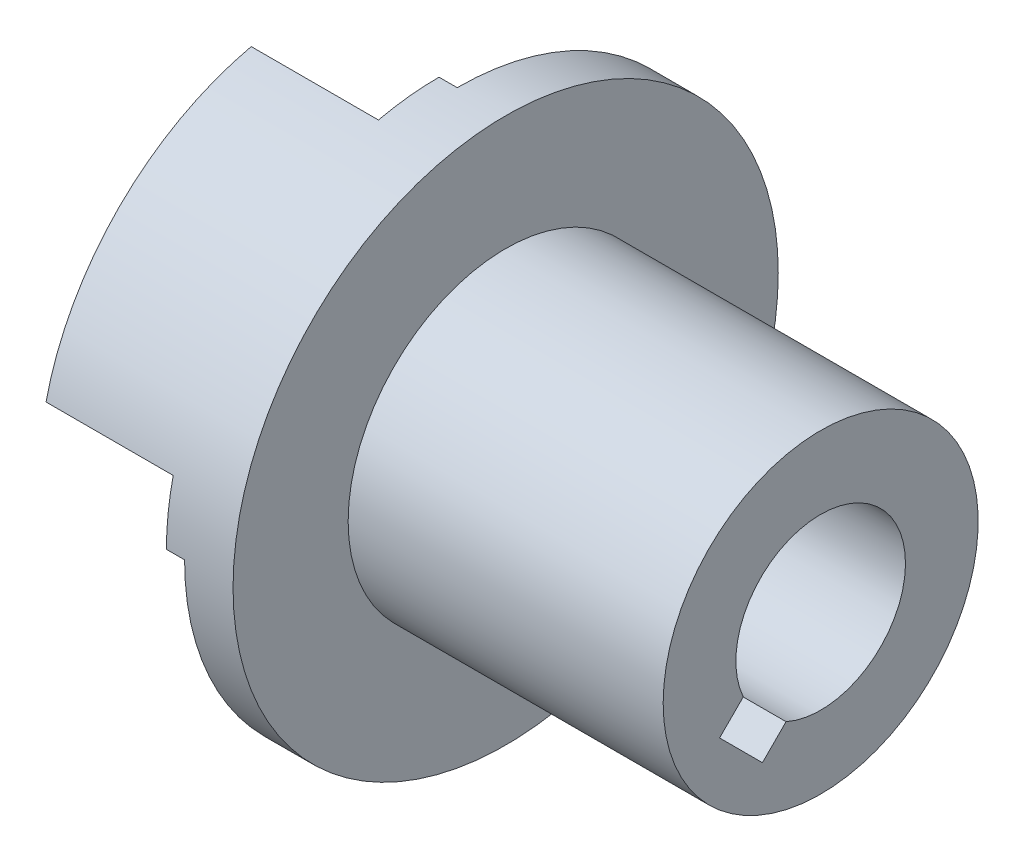
SolidWorks part; units mm, degrees
ref_plane "Спереди" through (0, 0, 0) normal (0, 0, 1) x (1, 0, 0)
ref_plane "Сверху" through (0, 0, 0) normal (0, 1, 0) x (1, 0, 0)
ref_plane "Справа" through (0, 0, 0) normal (1, 0, 0) x (0, 0, -1)
sketch "Эскиз1" plane through (0, 0, 0) normal (0, 0, 1) x (1, 0, 0)
  line L0 (0, 0) -> (112.9286, 0) construction
  line L1 (0, 22.5) -> (0, 7)
  line L2 (0, 7) -> (30, 7)
  line L3 (30, 7) -> (30, 13)
  line L4 (30, 13) -> (4, 13)
  line L5 (4, 13) -> (4, 22.5)
  line L6 (4, 22.5) -> (0, 22.5)
  dimension "l" = 30
  dimension "d1" = 26
  dimension "DD" = 45
  dimension "d" = 14
  dimension "l3" = 4
revolve "Повернуть1" add sketch "Эскиз1" angle 360 about L0
sketch "Эскиз7" plane through (0, 0, 0) normal (-1, 0, 0) x (0, 0, 1)
  line L0 (0, 22.5) -> (0, 14.1421)
  line L1 (22.5, 0) -> (14.1421, 0)
  line L4 (0, 14.1421) -> (14.1421, 0)
  circle A0 centre (0, 0) radius 22.5 construction
  arc A7 (22.5, 0) -> (0, 22.5) centre (0, 0) ccw
  dimension "D1" = 135
  dimension "B1/2" = 10
extrude "Бобышка-Вытянуть4" add sketch "Эскиз7" along normal blind 1.5
sketch "Эскиз9" plane through (-1.5, 0, 0) normal (-1, 0, 0) x (0, 0, 1)
  line L0 (5, 21.9374) -> (5, 9.1421)
  line L1 (5, 9.1421) -> (9.1421, 5)
  line L2 (9.1421, 5) -> (21.9374, 5)
  line L3 (0, 14.1421) -> (14.1421, 0) construction
  line L4 (0, 22.5) -> (0, 14.1421) construction
  line L5 (14.1421, 0) -> (22.5, 0) construction
  arc A0 (21.9374, 5) -> (5, 21.9374) centre (0, 0) ccw
  arc A1 (22.5, 0) -> (0, 22.5) centre (0, 0) ccw construction
  dimension "B" = 5
  dimension "BB" = 5
  dimension "B1/2" = 10
extrude "Бобышка-Вытянуть5" add sketch "Эскиз9" along normal blind 10.5
pattern_circular "Круговой массив2" count 2 over 360 about axis through (0, 0, 0) along (1, 0, 0) of "Бобышка-Вытянуть5", "Бобышка-Вытянуть4"
sketch "Эскиз10" plane through (30, 0, 0) normal (1, 0, 0) x (0, 0, -1)
  line L0 (0, 0) -> (0, -6.9906) construction
  line L1 (0, 0) -> (-8.8135, -8.8135) construction
  line L2 (1.7678, -1.7678) -> (-1.7678, 1.7678)
  line L3 (-1.7678, 1.7678) -> (-8.3439, -4.8083)
  line L4 (-8.3439, -4.8083) -> (-4.8083, -8.3439)
  line L5 (-4.8083, -8.3439) -> (1.7678, -1.7678)
  dimension "D1" = 45
  dimension "b" = 5
  dimension "(d/2)+t1" = 9.3
extrude "Вырез-Вытянуть3" cut sketch "Эскиз10" against normal through all
